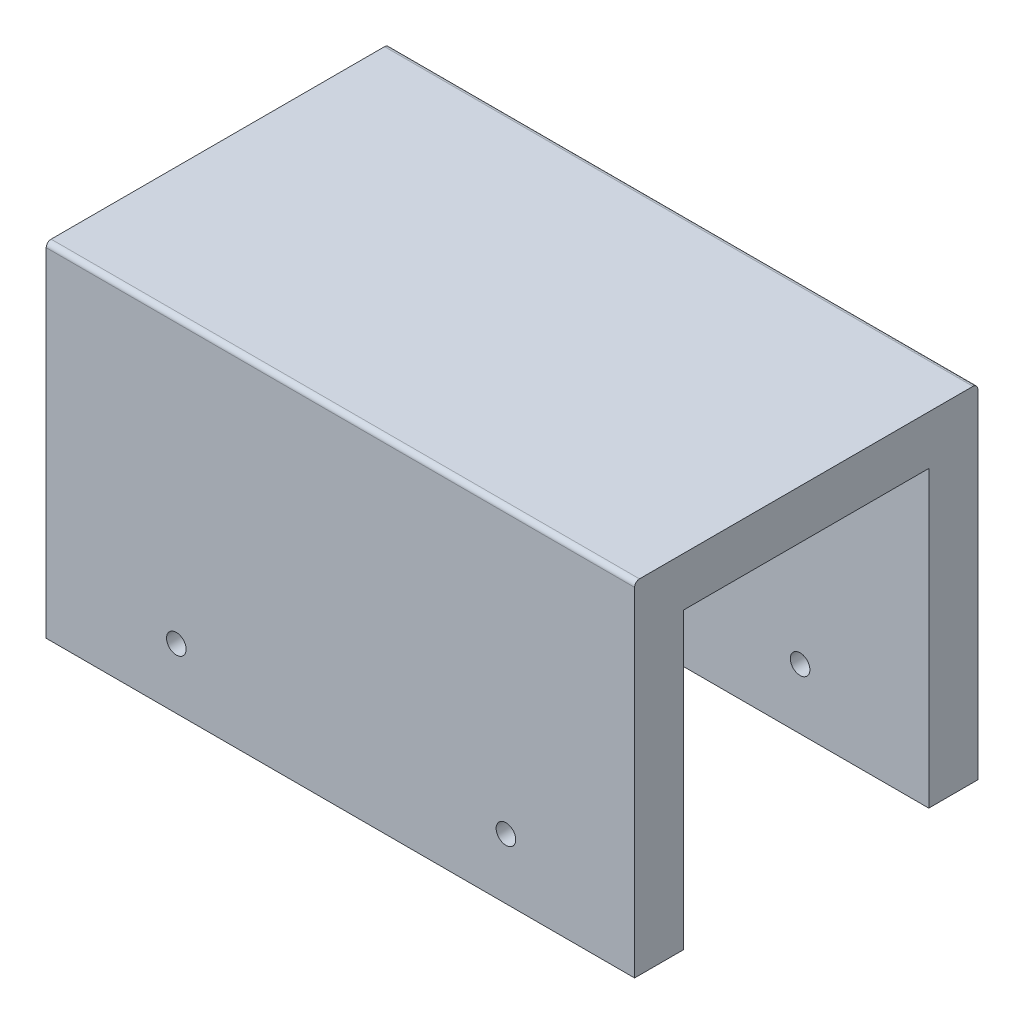
SolidWorks part; units mm, degrees
material "Acrylic (Medium-high impact)"
ref_plane "Front Plane" through (0, 0, 0) normal (0, 0, 1) x (1, 0, 0)
ref_plane "Top Plane" through (0, 0, 0) normal (0, 1, 0) x (1, 0, 0)
ref_plane "Right Plane" through (0, 0, 0) normal (1, 0, 0) x (0, 0, -1)
sketch "Sketch3" plane through (0, 0, 0) normal (1, 0, 0) x (0, 0, -1)
  line L1 (-25, 30) -> (25, 30)
  line L2 (-25, 30) -> (-25, -30)
  line L4 (25, 30) -> (25, -30)
  line L5 (-25, 30) -> (25, -30) construction
  line L6 (-25, -30) -> (25, 30) construction
  point P0 (0, 0)
  dimension "D1" = 50
  dimension "D2" = 60
extrude "Extrude-Thin1" add sketch "Sketch3" along normal blind 120 thin thin type one direction wall 10
sketch "Sketch5" plane through (0, 0, 35) normal (0, 0, 1) x (1, 0, 0)
  circle A0 centre (26.5366, -17.6865) radius 2
  circle A1 centre (93.7613, -17.6865) radius 2
  point P4 (89.9676, -17.6865)
  point P5 (27.9023, -17.6865)
  point P6 (93.7613, -17.6865)
  point P7 (23.9569, -17.6865)
  point P8 (27.2953, -17.6865)
  point P9 (26.5366, -17.6865)
  dimension "D1" = 4
  dimension "D2" = 4
extrude "Cut-Extrude1" cut sketch "Sketch5" against normal through all
fillet "Fillet1" radius 1 2 edges at (60, 40, -35) (60, 40, 35)
